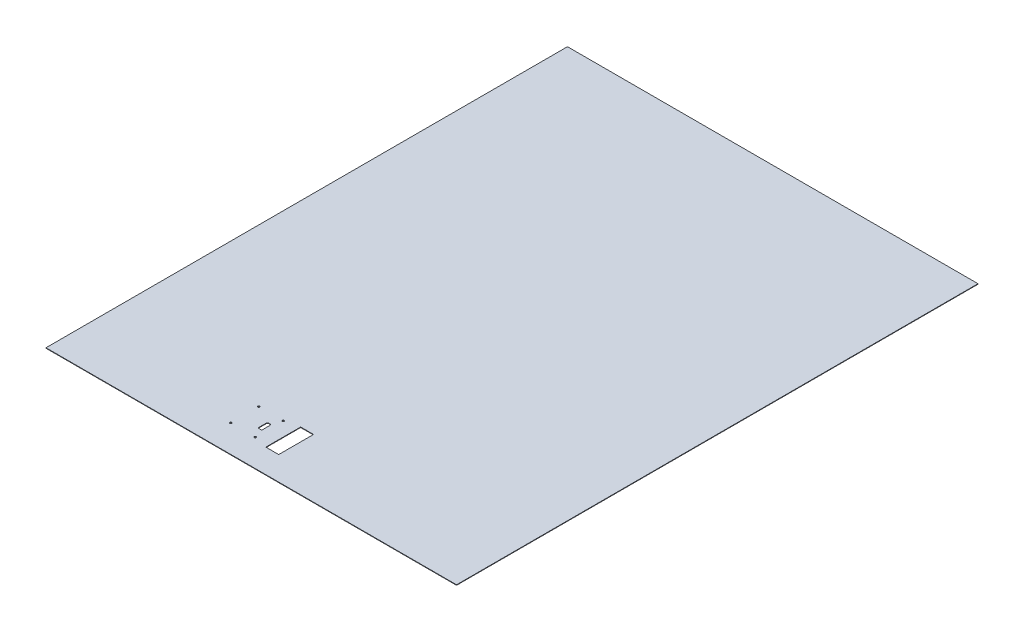
SolidWorks part; units mm, degrees
ref_plane "Front Plane" through (0, 0, 0) normal (0, 0, 1) x (1, 0, 0)
ref_plane "Top Plane" through (0, 0, 0) normal (0, 1, 0) x (1, 0, 0)
ref_plane "Right Plane" through (0, 0, 0) normal (1, 0, 0) x (0, 0, -1)
sketch "Sketch1" plane through (0, 0, 0) normal (0, 1, 0) x (1, 0, 0)
  line L1 (612.6065, -310.951) -> (-247.8935, -310.951)
  line L2 (612.6065, -310.951) -> (612.6065, 782.049)
  line L3 (612.6065, 782.049) -> (-247.8935, 782.049)
  line L4 (-247.8935, -310.951) -> (-247.8935, 782.049)
  dimension "D1" = 1093
  dimension "D2" = 860.5
extrude "Boss-Extrude1" add sketch "Sketch1" along normal blind 1
sketch "Sketch2" plane through (0, 1, 0) normal (0, 1, 0) x (1, 0, 0)
  line L0 (-247.8935, -310.951) -> (612.6065, -310.951) construction
  line L1 (162.8565, -187.951) -> (189.8565, -187.951)
  line L2 (162.8565, -187.951) -> (162.8565, -260.951)
  line L3 (162.8565, -260.951) -> (189.8565, -260.951)
  line L4 (189.8565, -187.951) -> (189.8565, -260.951)
  line L5 (612.6065, -310.951) -> (612.6065, 782.049) construction
  line L6 (-247.8935, 782.049) -> (-247.8935, -310.951) construction
  point P6 (176.3565, -260.951)
  point P9 (189.8565, -224.451)
  dimension "D1" = 27
  dimension "D2" = 73
  dimension "D3" = 50
  dimension "D4" = 422.75
  dimension "D5" = 410.75
extrude "Cut-Extrude1" cut sketch "Sketch2" against normal blind 1
sketch "Sketch3" plane through (0, 1, 0) normal (0, 1, 0) x (1, 0, 0)
  line L0 (189.8565, -187.951) -> (162.8565, -187.951) construction
  line L1 (162.8565, -260.951) -> (189.8565, -260.951) construction
  line L2 (162.8565, -187.951) -> (162.8565, -260.951) construction
  circle A0 centre (133.6565, -194.951) radius 2
  circle A1 centre (133.6565, -253.951) radius 2
  circle A2 centre (81.9765, -194.951) radius 2
  circle A3 centre (81.9765, -253.951) radius 2
  dimension "D1" = 4
  dimension "D2" = 4
  dimension "D3" = 4
  dimension "D4" = 4
  dimension "D5" = 7
  dimension "D6" = 7
  dimension "D7" = 29.2
  dimension "D8" = 29.2
  dimension "D9" = 7
  dimension "D10" = 7
  dimension "D11" = 51.68
  dimension "D12" = 51.68
extrude "Cut-Extrude2" cut sketch "Sketch3" against normal through all
sketch "Sketch4" plane through (0, 1, 0) normal (0, 1, 0) x (1, 0, 0)
  line L1 (127.7565, -214.451) -> (119.7565, -214.451)
  line L2 (127.7565, -214.451) -> (127.7565, -234.451)
  line L3 (127.7565, -234.451) -> (119.7565, -234.451)
  line L4 (119.7565, -214.451) -> (119.7565, -234.451)
  circle A0 centre (133.6565, -194.951) radius 2 construction
  circle A1 centre (133.6565, -253.951) radius 2 construction
  dimension "D1" = 20
  dimension "D2" = 8
  dimension "D3" = 19.5
  dimension "D4" = 19.5
  dimension "D5" = 5.9
extrude "Cut-Extrude3" cut sketch "Sketch4" against normal blind 1
fillet "Fillet1" radius 2 4 edges at (119.7565, 0.5, 214.451) (119.7565, 0.5, 234.451) (127.7565, 0.5, 234.451) (127.7565, 0.5, 214.451)
